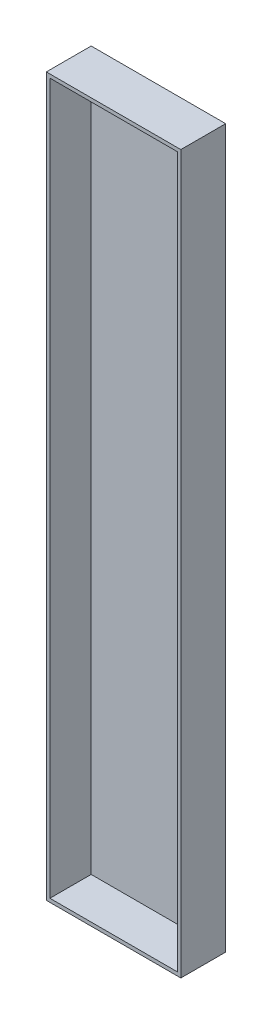
SolidWorks part; units mm, degrees
ref_plane "Plan de face" through (0, 0, 0) normal (0, 0, 1) x (1, 0, 0)
ref_plane "Plan de dessus" through (0, 0, 0) normal (0, 1, 0) x (1, 0, 0)
ref_plane "Plan de droite" through (0, 0, 0) normal (1, 0, 0) x (0, 0, -1)
sketch "Esquisse1" plane through (0, 0, 0) normal (0, 0, 1) x (1, 0, 0)
  line L1 (0, 0) -> (150, 0)
  line L2 (0, 0) -> (0, -800)
  line L3 (0, -800) -> (150, -800)
  line L4 (150, 0) -> (150, -800)
  dimension "D1" = 800
  dimension "D2" = 150
extrude "Boss.-Extru.1" add sketch "Esquisse1" along normal blind 50
sketch "Esquisse2" plane through (0, 0, 50) normal (0, 0, 1) x (1, 0, 0)
  line L0 (150, 0) -> (0, 0) construction
  line L1 (4, -4) -> (146, -4)
  line L2 (4, -4) -> (4, -796)
  line L3 (4, -796) -> (146, -796)
  line L4 (146, -4) -> (146, -796)
  line L5 (0, 0) -> (0, -800) construction
  line L6 (150, -800) -> (150, 0) construction
  line L7 (0, -800) -> (150, -800) construction
  dimension "D1" = 4
  dimension "D2" = 4
  dimension "D3" = 4
  dimension "D4" = 4
extrude "Enlèv. mat.-Extru.1" cut sketch "Esquisse2" against normal blind 46
